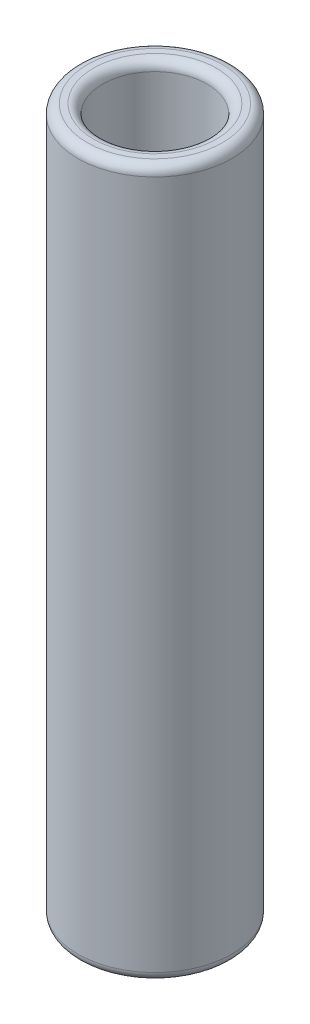
SolidWorks part; units mm, degrees
ref_plane "Front Plane" through (0, 0, 0) normal (0, 0, 1) x (1, 0, 0)
ref_plane "Top Plane" through (0, 0, 0) normal (0, 1, 0) x (1, 0, 0)
ref_plane "Right Plane" through (0, 0, 0) normal (1, 0, 0) x (0, 0, -1)
sketch "Sketch1" plane through (0, 0, 0) normal (0, 1, 0) x (1, 0, 0)
  circle A0 centre (0, 0) radius 2.5
  circle A1 centre (0, 0) radius 1.7
  dimension "D1" = 5
  dimension "D2" = 3.4
extrude "Boss-Extrude1" add sketch "Sketch1" along normal blind 23
fillet "Fillet1" radius 0.3 4 edges at (0, 0, 1.7) (0, 0, 2.5) (0, 23, 1.7) (0, 23, 2.5)
